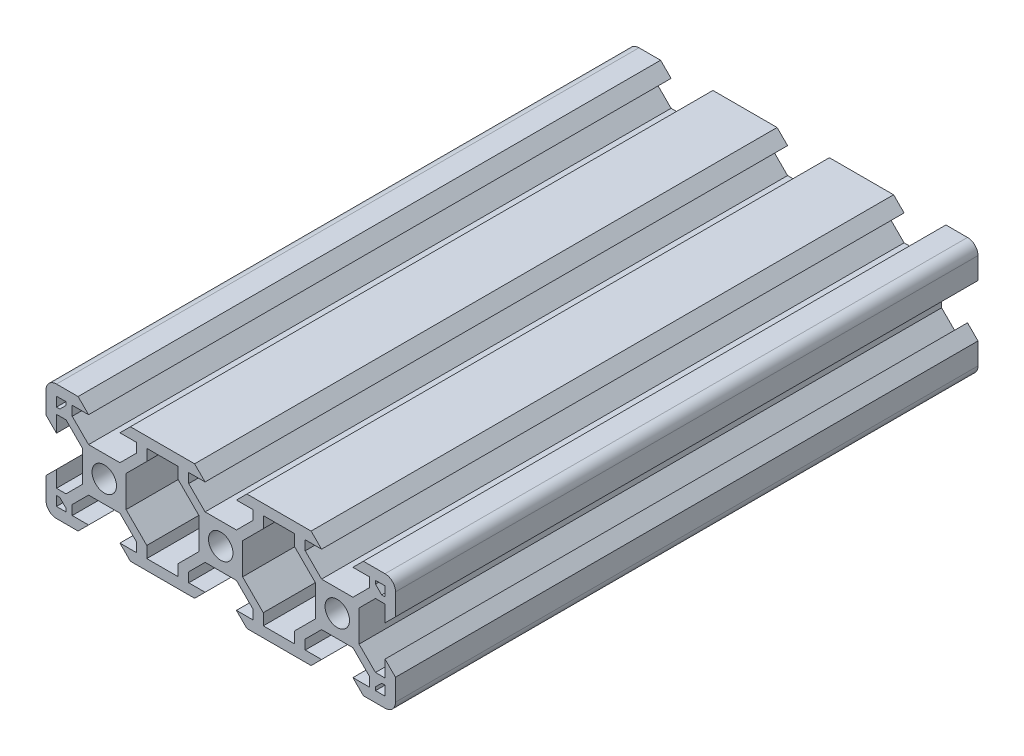
SolidWorks part; units mm, degrees
material "5052-H38, Barre (SS)"
ref_plane "Plan de face" through (0, 0, 0) normal (0, 0, 1) x (1, 0, 0)
ref_plane "Plan de dessus" through (0, 0, 0) normal (0, 1, 0) x (1, 0, 0)
ref_plane "Plan de droite" through (0, 0, 0) normal (1, 0, 0) x (0, 0, -1)
sketch "Esquisse1" plane through (0, 0, 0) normal (0, 0, 1) x (1, 0, 0)
  line L0 (0, 0) -> (-30, 0) construction
  line L1 (0, 0) -> (0, 10) construction
  line L2 (-20, 0) -> (-30, 10) construction
  line L3 (-20, 3.7507) -> (-22.69, 3.7507)
  line L4 (-22.69, 3.7507) -> (-25.4993, 6.56)
  line L5 (-25.4993, 6.56) -> (-25.4993, 8.2)
  line L6 (-25.4993, 8.2) -> (-22.69, 8.2)
  line L7 (-22.69, 8.2) -> (-24.49, 10)
  line L8 (-24.49, 10) -> (-28.2, 10)
  line L9 (-20, 0) -> (-20, 10) construction
  line L10 (-30, 4.49) -> (-30, 8.2)
  line L11 (-28.2, 2.69) -> (-30, 4.49)
  line L12 (-28.2, 5.4993) -> (-28.2, 2.69)
  line L13 (-26.56, 5.4993) -> (-28.2, 5.4993)
  line L14 (-23.7507, 2.69) -> (-26.56, 5.4993)
  line L15 (-23.7507, 0) -> (-23.7507, 2.69)
  line L16 (-28.2, 8.2) -> (-28.2, 6.5693)
  line L17 (-28.2, 6.5693) -> (-27.63, 6.5693)
  line L18 (-27.63, 6.5693) -> (-26.5693, 7.63)
  line L19 (-26.5693, 7.63) -> (-26.5693, 8.2)
  line L20 (-26.5693, 8.2) -> (-28.2, 8.2)
  line L21 (-23.7507, 0) -> (-23.7507, -2.69)
  line L22 (-23.7507, -2.69) -> (-26.56, -5.4993)
  line L23 (-26.56, -5.4993) -> (-28.2, -5.4993)
  line L24 (-28.2, -5.4993) -> (-28.2, -2.69)
  line L25 (-28.2, -2.69) -> (-30, -4.49)
  line L26 (-30, -4.49) -> (-30, -8.2)
  line L27 (-24.49, -10) -> (-28.2, -10)
  line L28 (-22.69, -8.2) -> (-24.49, -10)
  line L29 (-25.4993, -8.2) -> (-22.69, -8.2)
  line L30 (-25.4993, -6.56) -> (-25.4993, -8.2)
  line L31 (-22.69, -3.7507) -> (-25.4993, -6.56)
  line L32 (-20, -3.7507) -> (-22.69, -3.7507)
  line L33 (-26.5693, -7.63) -> (-27.63, -6.5693)
  line L34 (-27.63, -6.5693) -> (-28.2, -6.5693)
  line L35 (-28.2, -6.5693) -> (-28.2, -8.2)
  line L36 (-28.2, -8.2) -> (-26.5693, -8.2)
  line L37 (-26.5693, -8.2) -> (-26.5693, -7.63)
  line L38 (-2.69, -8.2) -> (-4.49, -10)
  line L39 (-2.69, 8.2) -> (-4.49, 10)
  line L40 (-7.3007, -8.2) -> (-7.3007, -6.24)
  line L41 (-7.3007, -6.24) -> (-3.7507, -2.69)
  line L42 (-3.7507, 2.69) -> (-3.7507, -2.69)
  line L43 (-7.3007, 6.24) -> (-3.7507, 2.69)
  line L44 (-7.3007, 8.2) -> (-7.3007, 6.24)
  line L45 (26.5693, 8.2) -> (28.2, 8.2)
  line L46 (26.5693, 7.63) -> (26.5693, 8.2)
  line L47 (27.63, 6.5693) -> (26.5693, 7.63)
  line L48 (28.2, 6.5693) -> (27.63, 6.5693)
  line L49 (28.2, 8.2) -> (28.2, 6.5693)
  line L50 (26.5693, -8.2) -> (26.5693, -7.63)
  line L51 (28.2, -8.2) -> (26.5693, -8.2)
  line L52 (28.2, -6.5693) -> (28.2, -8.2)
  line L53 (27.63, -6.5693) -> (28.2, -6.5693)
  line L54 (26.5693, -7.63) -> (27.63, -6.5693)
  line L55 (7.3007, 8.2) -> (7.3007, 6.24)
  line L56 (7.3007, 8.2) -> (12.6993, 8.2)
  line L57 (12.6993, 8.2) -> (12.6993, 6.24)
  line L58 (12.6993, 6.24) -> (16.2493, 2.69)
  line L59 (16.2493, 2.69) -> (16.2493, -2.69)
  line L60 (12.6993, -6.24) -> (16.2493, -2.69)
  line L61 (12.6993, -8.2) -> (12.6993, -6.24)
  line L62 (7.3007, -8.2) -> (12.6993, -8.2)
  line L63 (7.3007, -8.2) -> (7.3007, -6.24)
  line L64 (7.3007, -6.24) -> (3.7507, -2.69)
  line L65 (3.7507, 2.69) -> (3.7507, -2.69)
  line L66 (7.3007, 6.24) -> (3.7507, 2.69)
  line L67 (2.69, -8.2) -> (4.49, -10)
  line L68 (15.51, -10) -> (4.49, -10)
  line L69 (17.31, -8.2) -> (15.51, -10)
  line L70 (14.5007, -8.2) -> (17.31, -8.2)
  line L71 (14.5007, -6.56) -> (14.5007, -8.2)
  line L72 (17.31, -3.7507) -> (14.5007, -6.56)
  line L73 (20, -3.7507) -> (17.31, -3.7507)
  line L74 (20, -3.7507) -> (22.69, -3.7507)
  line L75 (22.69, -3.7507) -> (25.4993, -6.56)
  line L76 (25.4993, -6.56) -> (25.4993, -8.2)
  line L77 (25.4993, -8.2) -> (22.69, -8.2)
  line L78 (22.69, -8.2) -> (24.49, -10)
  line L79 (24.49, -10) -> (28.2, -10)
  line L80 (30, -4.49) -> (30, -8.2)
  line L81 (28.2, -2.69) -> (30, -4.49)
  line L82 (28.2, -5.4993) -> (28.2, -2.69)
  line L83 (26.56, -5.4993) -> (28.2, -5.4993)
  line L84 (0, 0) -> (-10, 10) construction
  line L85 (-17.31, 3.7507) -> (-14.5007, 6.56)
  line L86 (-14.5007, 6.56) -> (-14.5007, 8.2)
  line L87 (-14.5007, 8.2) -> (-17.31, 8.2)
  line L88 (-17.31, 8.2) -> (-15.51, 10)
  line L89 (-20, 3.7507) -> (-17.31, 3.7507)
  line L90 (-20, -3.7507) -> (-17.31, -3.7507)
  line L91 (-17.31, -3.7507) -> (-14.5007, -6.56)
  line L92 (-14.5007, -6.56) -> (-14.5007, -8.2)
  line L93 (-14.5007, -8.2) -> (-17.31, -8.2)
  line L94 (-17.31, -8.2) -> (-15.51, -10)
  line L95 (-10, 10) -> (-10, 0) construction
  line L96 (-15.51, 10) -> (-4.49, 10)
  line L97 (-15.51, -10) -> (-4.49, -10)
  line L98 (-7.3007, 8.2) -> (-12.6993, 8.2)
  line L99 (-12.6993, 8.2) -> (-12.6993, 6.24)
  line L100 (-12.6993, 6.24) -> (-16.2493, 2.69)
  line L101 (-16.2493, 2.69) -> (-16.2493, -2.69)
  line L102 (-20, 0) -> (-10, 10) construction
  line L103 (-17.31, 3.7507) -> (-16.2493, 2.69) construction
  line L104 (-12.6993, -6.24) -> (-16.2493, -2.69)
  line L105 (-12.6993, -8.2) -> (-12.6993, -6.24)
  line L106 (-7.3007, -8.2) -> (-12.6993, -8.2)
  line L107 (23.7507, -2.69) -> (26.56, -5.4993)
  line L108 (23.7507, 0) -> (23.7507, -2.69)
  line L109 (23.7507, 0) -> (23.7507, 2.69)
  line L110 (23.7507, 2.69) -> (26.56, 5.4993)
  line L111 (26.56, 5.4993) -> (28.2, 5.4993)
  line L112 (28.2, 5.4993) -> (28.2, 2.69)
  line L113 (28.2, 2.69) -> (30, 4.49)
  line L114 (30, 4.49) -> (30, 8.2)
  line L115 (24.49, 10) -> (28.2, 10)
  line L116 (22.69, 8.2) -> (24.49, 10)
  line L117 (25.4993, 8.2) -> (22.69, 8.2)
  line L118 (25.4993, 6.56) -> (25.4993, 8.2)
  line L119 (22.69, 3.7507) -> (25.4993, 6.56)
  line L120 (20, 3.7507) -> (22.69, 3.7507)
  line L121 (20, 3.7507) -> (17.31, 3.7507)
  line L122 (17.31, 3.7507) -> (14.5007, 6.56)
  line L123 (14.5007, 6.56) -> (14.5007, 8.2)
  line L124 (14.5007, 8.2) -> (17.31, 8.2)
  line L125 (17.31, 8.2) -> (15.51, 10)
  line L126 (15.51, 10) -> (4.49, 10)
  line L127 (2.69, 8.2) -> (4.49, 10)
  line L128 (-2.69, 8.2) -> (-5.4993, 8.2)
  line L129 (-5.4993, 8.2) -> (-5.4993, 6.56)
  line L130 (-5.4993, 6.56) -> (-2.69, 3.7507)
  line L131 (-2.69, 3.7507) -> (2.69, 3.7507)
  line L132 (5.4993, 6.56) -> (2.69, 3.7507)
  line L133 (5.4993, 8.2) -> (5.4993, 6.56)
  line L134 (5.4993, 8.2) -> (2.69, 8.2)
  line L135 (2.69, 8.2) -> (5.4993, 8.2)
  line L136 (5.4993, -8.2) -> (2.69, -8.2)
  line L137 (5.4993, -8.2) -> (5.4993, -6.56)
  line L138 (5.4993, -6.56) -> (2.69, -3.7507)
  line L139 (-2.69, -3.7507) -> (2.69, -3.7507)
  line L140 (-5.4993, -6.56) -> (-2.69, -3.7507)
  line L141 (-5.4993, -8.2) -> (-5.4993, -6.56)
  line L142 (-2.69, -8.2) -> (-5.4993, -8.2)
  circle A0 centre (0, 0) radius 2.1
  circle A1 centre (-20, 0) radius 2.1
  arc A2 (-28.2, 10) -> (-30, 8.2) centre (-28.2, 8.2) ccw
  arc A3 (-30, -8.2) -> (-28.2, -10) centre (-28.2, -8.2) ccw
  circle A4 centre (20, 0) radius 2.1
  arc A5 (30, -8.2) -> (28.2, -10) centre (28.2, -8.2) cw
  arc A6 (28.2, 10) -> (30, 8.2) centre (28.2, 8.2) cw
  point P26 (-27.0997, 7.0997)
  point P32 (-10, -10)
  point P55 (-10, -8.2)
  point P61 (-10, 8.2)
  point P106 (-16.7797, 3.2203)
  point P108 (-16.2493, 0)
  point P153 (0, 3.7507)
  point P154 (0, 3.7507)
  dimension "D3" = 4.2
  dimension "D1" = 30
  dimension "D2" = 10
  dimension "D5" = 20
  dimension "D6" = 1.5
  dimension "D7" = 1.64
  dimension "D8" = 1.8
  dimension "D9" = 5.38
  dimension "D10" = 1.07
  dimension "D12" = 45
  dimension "D15" = 1.96
  dimension "D4" = 2
  dimension "D11" = 2
  dimension "D13" = 2
  dimension "D14" = 2
extrude "Boss.-Extru.1" add sketch "Esquisse1" along normal mid plane 100 contours A6 L115 L116 L117 L118 L119 L120 L121 L122 L123 L124 L125 L126 L127 L134 L133 L132 L131 L130 L129 L128 L39 L96 L88 L87 L86 L85 L89 L3 L4 L5 L6 L7 L8 A2 L10 L11 L12 L13 L14 L15 L21 L22 L23 L24 L25 L26 A3 L27 L28 L29
